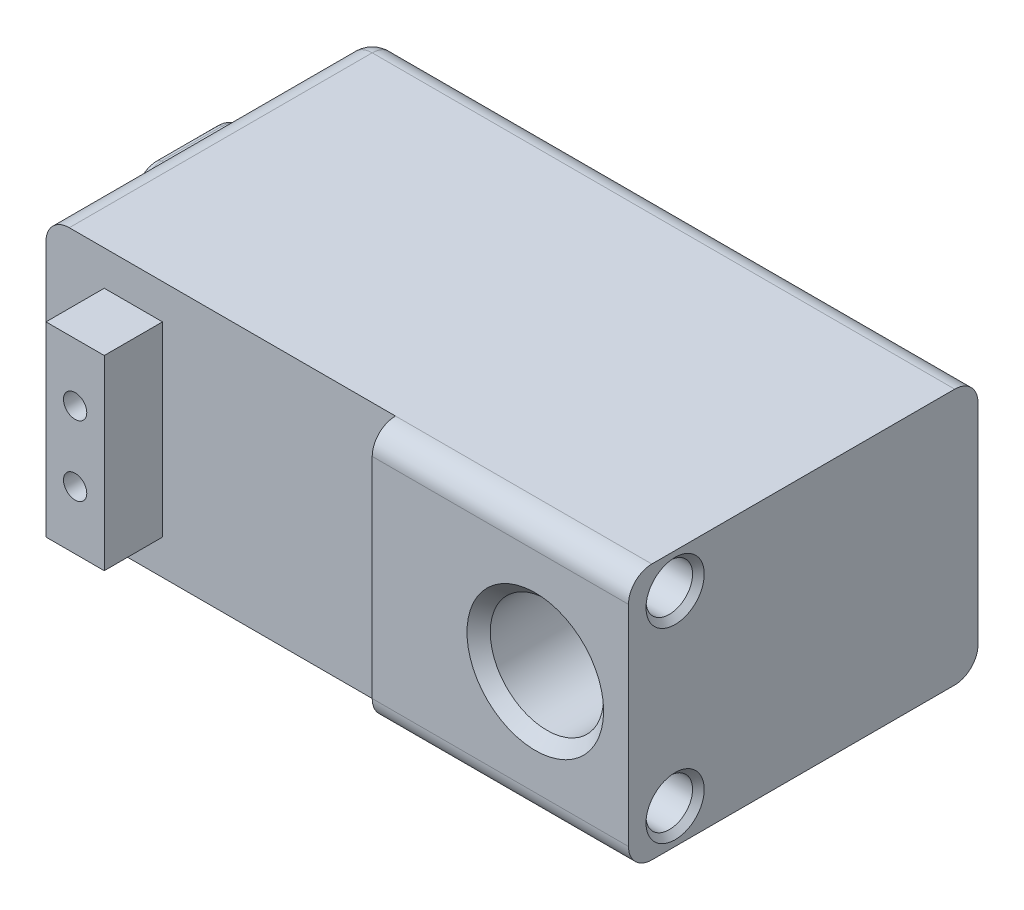
SolidWorks part; units mm, degrees
material "1060-H12"
ref_plane "Спереди" through (0, 0, 0) normal (0, 0, 1) x (1, 0, 0)
ref_plane "Сверху" through (0, 0, 0) normal (0, 1, 0) x (1, 0, 0)
ref_plane "Справа" through (0, 0, 0) normal (1, 0, 0) x (0, 0, -1)
ref_plane "Плоскость4" through (0, 22, 0) normal (0, 1, 0) x (1, 0, 0)
sketch "Эскиз1" plane through (0, 22, 0) normal (0, 1, 0) x (1, 0, 0)
  line L0 (-52, 30) -> (-52, 0)
  line L1 (-52, 0) -> (0, 0)
  line L2 (0, 0) -> (0, 30)
  line L3 (0, 30) -> (-52, 30)
  dimension "D1" = 30
extrude "Бобышка-Вытянуть1" add sketch "Эскиз1" against normal blind 22
sketch "Эскиз2" plane through (0, 0, 0) normal (0, -1, 0) x (1, 0, 0)
  line L0 (-22, -2) -> (-22, 0)
  line L1 (-22, 0) -> (-52, 0)
  line L2 (-52, 0) -> (-52, -2)
  line L3 (-52, -2) -> (-22, -2)
extrude "Вырез-Вытянуть1" cut sketch "Эскиз2" against normal through all
sketch "Эскиз3" plane through (-52, 0, 0) normal (-1, 0, 0) x (0, 0, 1)
  line L0 (-14.25, 17.4952) -> (-10.5, 11)
  line L1 (-10.5, 11) -> (-14.25, 4.5048)
  line L2 (-14.25, 4.5048) -> (-21.75, 4.5048)
  line L3 (-21.75, 4.5048) -> (-25.5, 11)
  line L4 (-25.5, 11) -> (-21.75, 17.4952)
  line L5 (-21.75, 17.4952) -> (-14.25, 17.4952)
extrude "Бобышка-Вытянуть2" add sketch "Эскиз3" along normal blind 4
sketch "Эскиз4" plane through (0, 0, -2) normal (0, 0, 1) x (1, 0, 0)
  line L0 (-47, 19) -> (-42, 19)
  line L1 (-42, 19) -> (-42, 3)
  line L2 (-42, 3) -> (-47, 3)
  line L3 (-47, 3) -> (-47, 19)
extrude "Бобышка-Вытянуть3" add sketch "Эскиз4" along normal blind 5
hole_wizard "Диаметр отверстия Ø4.0 (4)1" positions "Эскиз6" profile "Эскиз5" hole size "Ø4.0" standard "Ansi Metric"
sketch "Эскиз6" plane through (0, 0, 0) normal (1, 0, 0) x (0, 0, -1)
  point P0 (4, 3)
  point P1 (4, 19)
sketch "Эскиз5" plane through (0, 3, -4) normal (0, 1, 0) x (0, 0, -1)
  line L0 (0, 0) -> (0, 6)
  line L1 (0, 6) -> (2, 6)
  line L2 (2, 6) -> (2, 0)
  line L5 (2, 0) -> (0, 0)
  line L10 (0, 6) -> (-2, 6) construction
  line L11 (0, -6.35) -> (0, 107.95) construction
  dimension "Диаметр отверстия" = 4
  dimension "Глубина отверстия" = 6
  dimension "Угол заточки сверла" = 180
hole_wizard "Отверстие с зазором M81" positions "Эскиз8" profile "Эскиз7" hole size "M8" standard "Ansi Metric"
sketch "Эскиз8" plane through (0, 0, -30) normal (0, 0, -1) x (-1, 0, 0)
  point P0 (8, 11)
sketch "Эскиз7" plane through (-8, 11, -30) normal (1, 0, 0) x (0, 1, 0)
  line L0 (0, 0) -> (0, 33)
  line L1 (0, 33) -> (4.864, 33)
  line L2 (4.864, 33) -> (4.864, 0)
  line L5 (4.864, 0) -> (0, 0)
  line L11 (0, -6.35) -> (0, 107.95) construction
  dimension "Диаметр сквозного отверстия" = 9.728
  dimension "Глубина сквозного отверстия" = 33
hole_wizard "Диаметр отверстия Ø2.0 (2)1" positions "Эскиз10" profile "Эскиз9" hole size "Ø2.0" standard "Ansi Metric"
sketch "Эскиз10" plane through (0, 0, 3) normal (0, 0, 1) x (1, 0, 0)
  point P0 (-44.5, 14)
  point P1 (-44.5, 8)
sketch "Эскиз9" plane through (-44.5, 14, 3) normal (1, 0, 0) x (0, -1, 0)
  line L0 (0, 0) -> (0, 2)
  line L1 (0, 2) -> (1, 2)
  line L2 (1, 2) -> (1, 0)
  line L5 (1, 0) -> (0, 0)
  line L10 (0, 2) -> (-1, 2) construction
  line L11 (0, -6.35) -> (0, 107.95) construction
  dimension "Диаметр отверстия" = 2
  dimension "Глубина отверстия" = 2
  dimension "Угол заточки сверла" = 180
hole_wizard "Диаметр отверстия Ø8.0 (8)1" positions "Эскиз12" profile "Эскиз11" hole size "Ø8.0" standard "Ansi Metric"
sketch "Эскиз12" plane through (-56, 0, 0) normal (-1, 0, 0) x (0, 0, 1)
  point P0 (-18, 11)
sketch "Эскиз11" plane through (-56, 11, -18) normal (0, 1, 0) x (0, 0, 1)
  line L0 (0, 0) -> (0, 2)
  line L1 (0, 2) -> (4, 2)
  line L2 (4, 2) -> (4, 1)
  line L3 (4, 1) -> (5, 0)
  line L5 (5, 0) -> (0, 0)
  line L6 (-4, 1) -> (-5, 0) construction
  line L10 (0, 2) -> (-4, 2) construction
  line L11 (0, -6.35) -> (0, 107.95) construction
  dimension "Диаметр отверстия" = 8
  dimension "Глубина отверстия" = 2
  dimension "Диаметр передней зенковки" = 10
  dimension "Угол передней зенковки" = 90
  dimension "Угол заточки сверла" = 180
fillet "Скругление1" radius 2 13 edges at (-52, 0, -16) (-26, 0, -30) (-52, 11, -30) (-26, 22, -30) (-52, 22, -16) (-11, 22, 0) (-11, 0, 0) (-54, 17.4952, -21.75) (-54, 11, -25.5) (-54, 17.4952, -14.25) (-54, 11, -10.5) (-54, 4.5048, -14.25) (-54, 4.5048, -21.75)
chamfer "Фаска1" distance 1 angle 45 2 edges at (-3.136, 11, 0) (-12.864, 11, -30)
chamfer "Фаска2" distance 0.5 angle 45 2 edges at (0, 19, -6) (0, 3, -6)
fillet "Скругление2" radius 0.5 12 edges at (-56, 4.7728, -14.4047) (-56, 7.7524, -12.375) (-56, 4.5048, -18) (-56, 11, -10.8094) (-56, 4.7728, -21.5953) (-56, 14.2476, -12.375) (-56, 7.7524, -23.625) (-56, 17.2272, -14.4047) (-56, 11, -25.1906) (-56, 17.4952, -18) (-56, 14.2476, -23.625) (-56, 17.2272, -21.5953)
